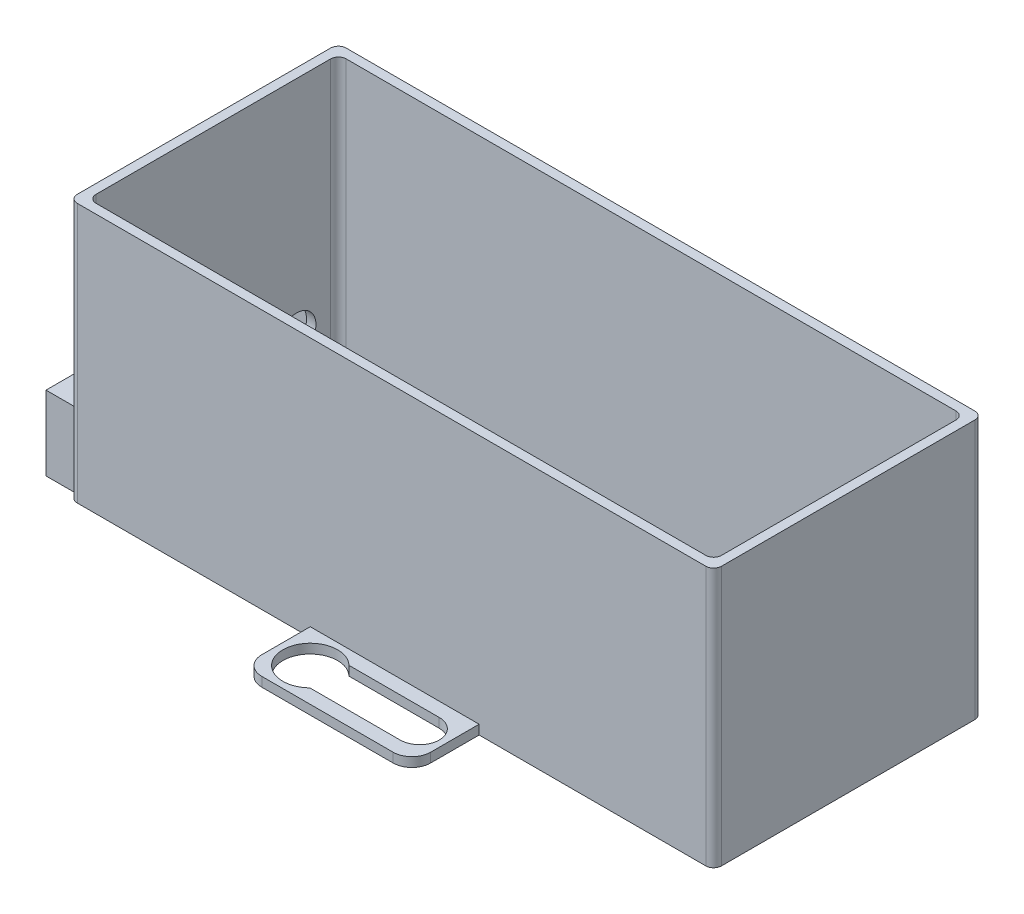
SolidWorks part; units mm, degrees
ref_plane "Plano frontal" through (0, 0, 0) normal (0, 0, 1) x (1, 0, 0)
ref_plane "Plano superior" through (0, 0, 0) normal (0, 1, 0) x (1, 0, 0)
ref_plane "Plano direito" through (0, 0, 0) normal (1, 0, 0) x (0, 0, -1)
sketch "Esboço2" plane through (0, 0, 0) normal (0, 1, 0) x (1, 0, 0)
  line L1 (-40, -16) -> (40, -16)
  line L2 (-40, -16) -> (-40, 16)
  line L3 (-40, 16) -> (40, 16)
  line L4 (40, -16) -> (40, 16)
  line L5 (-40, -16) -> (40, 16) construction
  line L6 (-40, 16) -> (40, -16) construction
  point P0 (0, 0)
  dimension "D1" = 80
  dimension "D2" = 32
extrude "Ressalto-extrusão1" add sketch "Esboço2" along normal blind 32
shell "Casca2" thickness 1.2
sketch "Esboço5" plane through (-41.2, 0, 0) normal (-1, 0, 0) x (0, 0, 1)
  line L0 (7.3525, 0.935) -> (7.3525, 3.535) construction
  line L1 (3.9775, 3.535) -> (10.7275, 3.535)
  line L2 (7.3525, 0.535) -> (7.3525, 0.935)
  line L3 (11.1275, 3.135) -> (11.1275, 2.5874)
  line L4 (-17.1999, -1.0202) -> (17.2001, -1.0202)
  line L5 (17.2001, -1.0202) -> (17.2001, 32)
  line L6 (17.2001, 32) -> (-17.1999, 32)
  line L7 (-17.1999, 32) -> (-17.1999, -1.0202)
  line L8 (10.8489, 1.8948) -> (10.2227, 1.2425)
  line L9 (9.5013, 0.935) -> (5.2037, 0.935)
  line L10 (3.8561, 1.8948) -> (4.4824, 1.2425)
  line L11 (3.5775, 3.135) -> (3.5775, 2.5874)
  arc A0 (10.2227, 1.2425) -> (9.5013, 0.935) centre (9.5013, 1.935) cw
  arc A1 (4.4824, 1.2425) -> (5.2037, 0.935) centre (5.2037, 1.935) ccw
  arc A2 (11.1275, 2.5874) -> (10.8489, 1.8948) centre (10.1275, 2.5874) cw
  arc A3 (3.8561, 1.8948) -> (3.5775, 2.5874) centre (4.5775, 2.5874) cw
  arc A4 (10.7275, 3.535) -> (11.1275, 3.135) centre (10.7275, 3.135) cw
  arc A5 (3.5775, 3.135) -> (3.9775, 3.535) centre (3.9775, 3.135) cw
  dimension "D3" = 1
  dimension "D4" = 0.4
  dimension "D1" = 7.55
  dimension "D2" = 2.6
extrude "Corte-extrusão2" cut sketch "Esboço5" against normal blind 32 contours L9 L0 L1 A5 L11 A3 L10 A1 | L0 L9 A0 L8 A2 L3 A4 L1
sketch "Esboço9" plane through (0, 0, 0) normal (0, 1, 0) x (1, 0, 0)
  line L0 (-10.6731, -8.6328) -> (-10.2731, -8.6328)
  line L1 (-27.1704, 1.8201) -> (-31.1704, 1.8201)
  line L2 (-27.1704, 1.8201) -> (-27.1704, 3.0201)
  line L3 (-27.1704, 3.0201) -> (-31.1704, 3.0201)
  line L4 (40, -16) -> (40, 16)
  line L5 (40, 16) -> (-40, 16)
  line L6 (-40, 16) -> (-40, -16)
  line L7 (-40, -16) -> (40, -16)
  line L8 (40, -16) -> (40, 16)
  line L9 (40, 16) -> (-40, 16)
  line L10 (-40, 16) -> (-40, -16)
  line L11 (-40, -16) -> (40, -16)
  line L12 (-31.1704, 1.8201) -> (-31.1704, 3.0201)
  line L13 (-13.0731, -6.6328) -> (-10.6731, -6.6328)
  line L14 (-13.0731, -6.6328) -> (-13.0731, -10.6328)
  line L15 (-13.0731, -10.6328) -> (-10.6731, -10.6328)
  line L16 (-10.6731, -6.6328) -> (-10.6731, -10.6328)
  line L17 (-10.2731, -8.6328) -> (24.5269, -8.6328)
  line L18 (24.5269, -8.6328) -> (24.5269, -12.6328)
  line L19 (-8.0863, -16.0004) -> (-8.0863, 9.9996)
  line L20 (24.5269, -8.6328) -> (25.7251, -8.6328)
  line L21 (24.5269, -8.6328) -> (24.5269, -12.6328)
  line L22 (24.5269, -12.6328) -> (25.7251, -12.6328)
  line L23 (25.7251, -8.6328) -> (25.7251, -12.6328)
  line L24 (-8.0863, 9.9996) -> (4.0167, 9.9996)
  line L25 (4.0167, 9.9996) -> (8.0167, 9.9996)
  line L26 (4.0167, 9.9996) -> (4.0167, 11.1996)
  line L27 (4.0167, 11.1996) -> (8.0167, 11.1996)
  line L28 (8.0167, 9.9996) -> (8.0167, 11.1996)
  line L29 (40.0006, -16.0004) -> (40.0006, 15.9996)
  line L30 (40.0006, 15.9996) -> (-39.9994, 15.9996)
  line L31 (-39.9994, 15.9996) -> (-39.9994, -16.0004)
  line L32 (-39.9994, -16.0004) -> (40.0006, -16.0004)
  dimension "D2" = 0.4
  dimension "D3" = 34.8
  dimension "D4" = 4
  dimension "D5" = 4
  dimension "D6" = 1.2
  dimension "D1" = 0
extrude "Ressalto-extrusão2" add sketch "Esboço9" along normal blind 1.2 contours L12 L1 L2 L3 | L16 L13 L14 L15 | L25 L28 L27 L26 | L23 L20 L18 L22
sketch "Esboço13" plane through (0, 0, 0) normal (0, 1, 0) x (1, 0, 0)
  text T0 "TP4056               ESP"
extrude "Corte-extrusão6" cut sketch "Esboço13" against normal blind 0.4
fillet "Filete1" radius 1 8 edges at (40, 16, 16) (40, 16, -16) (-40, 16, 16) (41.2, 15.4, -17.2) (41.2, 15.4, 17.2) (-41.2, 15.4, 17.2) (-41.2, 15.4, -17.2) (-40, 16, -16)
sketch "Esboço14" plane through (0, -1.2, 0) normal (0, -1, 0) x (1, 0, 0)
  line L2 (41.2, 16.2) -> (41.2, -16.2) construction
  line L3 (40.2, -17.2) -> (-40.2, -17.2) construction
  line L8 (-40.2, -17.2) -> (40.2, -17.2)
  line L9 (41.2, -16.2) -> (41.2, 16.2)
  line L10 (40.2, 17.2) -> (-40.2, 17.2)
  line L11 (-41.2, 16.2) -> (-41.2, -16.2)
  line L12 (-40.2, -17.2) -> (40.2, -17.2)
  line L13 (41.2, -16.2) -> (41.2, 16.2)
  line L14 (40.2, 17.2) -> (-40.2, 17.2)
  line L20 (0, 17.2) -> (-11.2, 17.2)
  line L21 (0, 17.2) -> (-7.2, 17.2)
  line L22 (-7.2, 17.2) -> (7.2, 17.2)
  line L23 (-11.2, 17.2) -> (11.2, 17.2)
  line L28 (11.2, 17.2) -> (11.2, 25.8)
  line L29 (11.2, 21.5) -> (10.4, 21.5)
  line L31 (-0.4, -25.8) -> (-7.6, -25.8)
  line L32 (-7.6, -25.8) -> (6.8, -25.8)
  line L36 (-10.4, 17.2) -> (11.2, 17.2)
  line L37 (-10.4, 17.2) -> (-10.4, 25.8)
  line L38 (-10.4, 25.8) -> (11.2, 25.8)
  line L39 (11.2, 17.2) -> (11.2, 25.8)
  line L40 (7.9, 24) -> (-3.6505, 24)
  line L41 (-11.6, -25.8) -> (10.8, -25.8)
  line L42 (-3.6505, 19) -> (7.9, 19)
  line L43 (10.8, -25.8) -> (10.8, -17.2)
  line L44 (10.8, -21.5) -> (10, -21.5)
  line L45 (-10.8, -25.8) -> (10.8, -25.8)
  line L46 (-10.8, -25.8) -> (-10.8, -17.2)
  line L47 (-10.8, -17.2) -> (10.8, -17.2)
  line L48 (10.8, -25.8) -> (10.8, -17.2)
  line L49 (7.5, -19) -> (-4.0505, -19)
  line L50 (-4.0505, -24) -> (7.5, -24)
  arc A6 (40.2, -17.2) -> (41.2, -16.2) centre (40.2, -16.2) ccw
  arc A7 (41.2, 16.2) -> (40.2, 17.2) centre (40.2, 16.2) ccw
  arc A8 (-40.2, 17.2) -> (-41.2, 16.2) centre (-40.2, 16.2) ccw
  arc A9 (-41.2, -16.2) -> (-40.2, -17.2) centre (-40.2, -16.2) ccw
  arc A10 (40.2, -17.2) -> (41.2, -16.2) centre (40.2, -16.2) ccw
  arc A11 (41.2, 16.2) -> (40.2, 17.2) centre (40.2, 16.2) ccw
  arc A13 (-40.5001, -16.5907) -> (-39.5001, -17.5907) centre (-39.5001, -16.5907) ccw
  arc A14 (7.9, 19) -> (7.9, 24) centre (7.9, 21.5) ccw
  arc A15 (-3.6505, 24) -> (-3.6505, 19) centre (-6.1, 21.5) ccw
  arc A16 (7.5, -24) -> (7.5, -19) centre (7.5, -21.5) ccw
  arc A17 (-4.0505, -19) -> (-4.0505, -24) centre (-6.5, -21.5) ccw
  dimension "D1" = 0
extrude "Ressalto-extrusão7" add sketch "Esboço14" against normal blind 1.2
fillet "Filete4" radius 2.4 4 edges at (11.2, -0.6, 25.8) (-10.4, -0.6, 25.8) (10.8, -0.6, -25.8) (-10.8, -0.6, -25.8)
sketch "Esboço18" plane through (-41.2, 0, 0) normal (-1, 0, 0) x (0, 0, 1)
  line L0 (15, 0) -> (15, 7.1095)
  line L1 (16.2, -1.2) -> (-16.2, -1.2)
  line L2 (16.2, -1.2) -> (16.2, 8.3095)
  line L3 (16.2, 8.3095) -> (-16.2, 8.3095)
  line L4 (-16.2, -1.2) -> (16.2, -1.2)
  line L5 (16.2, -1.2) -> (16.2, 32)
  line L6 (16.2, 32) -> (-16.2, 32)
  line L7 (-16.2, 32) -> (-16.2, -1.2)
  line L8 (-16.2, -1.2) -> (16.2, -1.2)
  line L9 (16.2, -1.2) -> (16.2, 32)
  line L10 (16.2, 32) -> (-16.2, 32)
  line L11 (-16.2, 32) -> (-16.2, -1.2)
  line L12 (-16.2, -1.2) -> (-16.2, 8.3095)
  line L13 (15, 7.1095) -> (-15, 7.1095)
  line L14 (-15, 0) -> (-15, 7.1095)
  line L15 (15, 0) -> (-15, 0)
  line M21 (-16.2, -1.2) -> (16.2, -1.2)
  line M22 (16.2, -1.2) -> (16.2, 32)
  line M24 (-16.2, 32) -> (-16.2, -1.2)
  dimension "D2" = 1.2
  dimension "D1" = 0
extrude "Ressalto-extrusão8" add sketch "Esboço18" along normal blind 4 contours L3 L0 L15 L14 L13 M22 M24 M21
sketch "Esboço19" plane through (-41.2, 0, 0) normal (-1, 0, 0) x (0, 0, 1)
  line L0 (7.3525, 3.535) -> (-10.6255, 3.535)
  line L1 (3.9775, 3.535) -> (10.7275, 3.535) construction
  circle A0 centre (-10.6255, 3.535) radius 2.5
extrude "Corte-extrusão9" cut sketch "Esboço19" against normal blind 4
